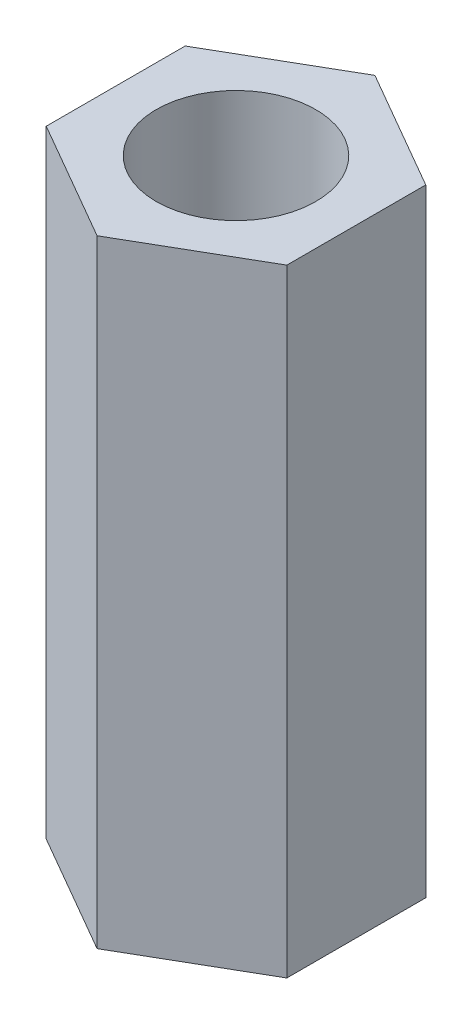
SolidWorks part; units mm, degrees
ref_plane "前视基准面" through (0, 0, 0) normal (0, 0, 1) x (1, 0, 0)
ref_plane "上视基准面" through (0, 0, 0) normal (0, 1, 0) x (1, 0, 0)
ref_plane "右视基准面" through (0, 0, 0) normal (1, 0, 0) x (0, 0, -1)
sketch "草图1" plane through (0, 0, 0) normal (0, 1, 0) x (1, 0, 0)
  line L1 (0, 2.7) -> (-2.3383, 1.35)
  line L2 (-2.3383, 1.35) -> (-2.3383, -1.35)
  line L3 (-2.3383, -1.35) -> (0, -2.7)
  line L4 (0, -2.7) -> (2.3383, -1.35)
  line L5 (2.3383, -1.35) -> (2.3383, 1.35)
  line L6 (2.3383, 1.35) -> (0, 2.7)
  circle A0 centre (0, 0) radius 2.7 construction
  circle A1 centre (0, 0) radius 1.55
  dimension "D1" = 3.1
extrude "凸台-拉伸1" add sketch "草图1" along normal blind 12
